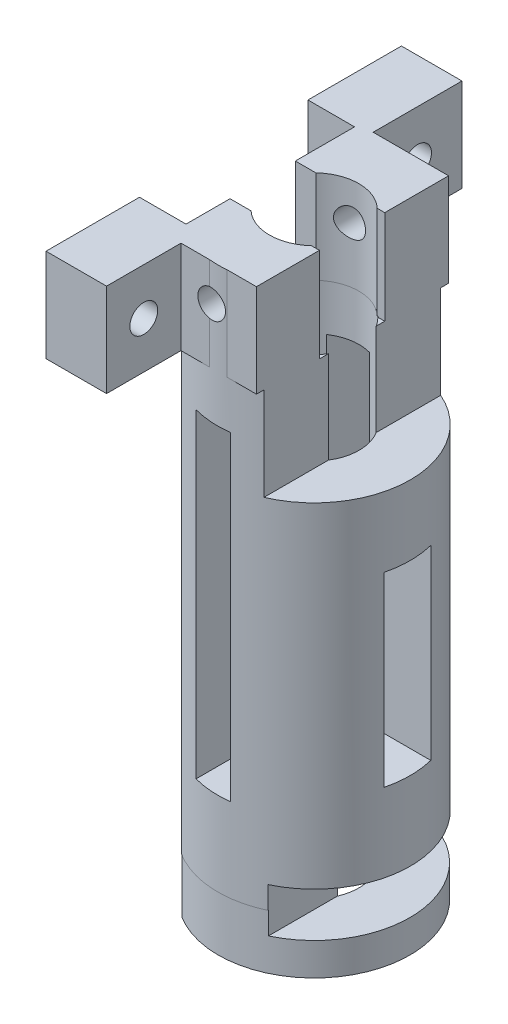
SolidWorks part; units mm, degrees
ref_plane "前基準面" through (0, 0, 0) normal (0, 0, 1) x (1, 0, 0)
ref_plane "上基準面" through (0, 0, 0) normal (0, 1, 0) x (1, 0, 0)
ref_plane "右基準面" through (0, 0, 0) normal (1, 0, 0) x (0, 0, -1)
sketch "草圖1" plane through (0, 0, 0) normal (0, 1, 0) x (1, 0, 0)
  circle A0 centre (0, 0) radius 9.68
  dimension "D1" = 19.36
extrude "伸長-薄件1" add sketch "草圖1" along normal blind 116.68 thin
ref_plane "平面1" through (-21, 0, 0) normal (1, 0, 0) x (0, 0, -1)
sketch "草圖11" plane through (0, 116.68, 0) normal (0, 1, 0) x (1, 0, 0)
  line L0 (-993.1634, -44.2358) -> (49006.8366, -44.2358) construction
  line L2 (35.2085, 30.7642) -> (8.2085, 30.7642)
  line L3 (35.2085, 30.7642) -> (35.2085, -119.2358)
  line L4 (35.2085, -119.2358) -> (8.2085, -119.2358)
  line L5 (8.2085, 30.7642) -> (8.2085, -119.2358)
  line L6 (35.2085, 30.7642) -> (8.2085, -119.2358) construction
  line L7 (35.2085, -119.2358) -> (8.2085, 30.7642) construction
  circle A0 centre (0, 0) radius 20.68 construction
  point P1 (21.7085, -44.2358)
  dimension "D1" = 150
  dimension "D2" = 27
  dimension "D3" = 30.7642
extrude "除料-伸長3" cut sketch "草圖11" against normal blind 40
ref_plane "平面2" through (0, 0, 21) normal (0, 0, 1) x (1, 0, 0)
sketch "草圖13" plane through (0, 0, 21) normal (0, 0, 1) x (1, 0, 0)
  line L0 (-21, -22.649) -> (-21, 22.649) construction
  line L1 (-21, 122.7847) -> (-11, 122.7847)
  line L2 (-21, 122.7847) -> (-21, -5.5603)
  line L3 (-21, -5.5603) -> (-11, -5.5603)
  line L4 (-11, 122.7847) -> (-11, -5.5603)
  dimension "D1" = 10
extrude "除料-伸長7" cut sketch "草圖13" against normal through all
sketch "草圖15" plane through (0, 0, 21) normal (0, 0, 1) x (1, 0, 0)
  line L0 (-1.3957, -883.32) -> (-1.3957, 49116.68) construction
  line L1 (8.2085, 116.68) -> (-11, 116.68) construction
  line L2 (-11, 0) -> (20.68, 0) construction
  line L3 (2.6043, 86.68) -> (-5.3957, 86.68)
  line L4 (2.6043, 86.68) -> (2.6043, 18)
  line L5 (2.6043, 18) -> (-5.3957, 18)
  line L6 (-5.3957, 86.68) -> (-5.3957, 18)
  line L7 (2.6043, 86.68) -> (-5.3957, 18) construction
  line L8 (2.6043, 18) -> (-5.3957, 86.68) construction
  point P1 (-1.3957, 52.34)
  point P5 (-1.3957, 116.68)
  dimension "D1" = 30
  dimension "D2" = 18
  dimension "D3" = 8
extrude "除料-伸長9" cut sketch "草圖15" against normal blind 48
sketch "草圖16" plane through (8.2085, 0, 0) normal (1, 0, 0) x (0, 0, -1)
  line L0 (20.68, 86.68) -> (20.68, 116.68) construction
  line L1 (5.1306, 116.68) -> (20.68, 116.68)
  line L2 (5.1306, 116.68) -> (5.1306, 96.68)
  line L3 (5.1306, 96.68) -> (20.68, 96.68)
  line L4 (20.68, 116.68) -> (20.68, 96.68)
  line L5 (-5.1306, 76.68) -> (-5.1306, 116.68) construction
  line L6 (-5.1306, 96.68) -> (-20.59, 96.68)
  line L7 (-5.1306, 96.68) -> (-5.1306, 116.68)
  line L8 (-5.1306, 116.68) -> (-20.59, 116.68)
  line L9 (-20.59, 96.68) -> (-20.59, 116.68)
  line L10 (-17.5118, 116.68) -> (-20.68, 116.68) construction
  dimension "D1" = 20
extrude "填料-伸長4" add sketch "草圖16" against normal blind 19.2
sketch "草圖17" plane through (0, 116.68, 0) normal (0, 1, 0) x (1, 0, 0)
  line L0 (-1009.59, 0) -> (48990.41, 0) construction
  line L1 (8.2085, 20.68) -> (8.2085, 5.1306) construction
  line L2 (8.2085, 6.97) -> (-11, 6.97)
  line L3 (8.2085, 6.97) -> (8.2085, -7.06)
  line L4 (8.2085, -7.06) -> (-11, -7.06)
  line L5 (-11, 6.97) -> (-11, -7.06)
  line L6 (-11, -17.5118) -> (-11, 17.5118) construction
  line L7 (-10.9915, -20.59) -> (-1.9273, -20.59) construction
  arc A0 (-8.2085, 5.1306) -> (-8.2085, -5.1306) centre (0, 0) ccw construction
  point P6 (-9.68, 0)
  dimension "D1" = 14.03
  dimension "D2" = 13.53
extrude "除料-伸長10" cut sketch "草圖17" against normal blind 20.2
sketch "草圖18" plane through (0, 0, 0) normal (0, -1, 0) x (1, 0, 0)
  circle A0 centre (0, 0) radius 9.59
extrude "除料-伸長11" cut sketch "草圖18" against normal through all
sketch "草圖21" plane through (0, 0, -20.68) normal (0, 0, -1) x (-1, 0, 0)
  line L0 (1.3915, 96.68) -> (1.3915, 105.73) construction
  line L1 (0, 96.68) -> (10.9915, 96.68) construction
  line L2 (1.3915, 105.73) -> (1.3915, 108.73) construction
  circle A0 centre (1.3915, 108.73) radius 2.985
  dimension "D3" = 5.97
  dimension "D1" = 9.05
  dimension "D2" = 3
extrude "除料-伸長12" cut sketch "草圖21" against normal blind 55.2
sketch "草圖23" plane through (0, 0, -20.68) normal (0, 0, -1) x (-1, 0, 0)
  line L0 (1.3915, 105.745) -> (1.3915, -11.785) construction
  circle A0 centre (1.3915, 108.73) radius 2.985 construction
  dimension "D1" = 117.53
sketch "草圖24" plane through (0, 0, 0) normal (0, -1, 0) x (1, 0, 0)
  circle A0 centre (0, 0) radius 9.59
extrude "伸長-薄件2" add sketch "草圖24" along normal blind 55.2 thin
sketch "草圖25" plane through (0, 0, 21) normal (0, 0, 1) x (1, 0, 0)
  line L0 (-1.3915, -11.785) -> (22.6124, -11.785)
  line L1 (22.6124, -11.785) -> (22.6124, -63.8733)
  line L2 (-22.7495, -63.8733) -> (22.6124, -63.8733)
  line L3 (-22.7495, -63.8733) -> (-22.7495, -11.785)
  line L4 (-22.7495, -11.785) -> (-1.3915, -11.785)
extrude "除料-伸長13" cut sketch "草圖25" against normal blind 55.2
sketch "草圖26" plane through (0, 0, 0) normal (0, 1, 0) x (1, 0, 0)
  line L0 (-21, -22.649) -> (-21, 22.649) construction
  line L1 (-10.9915, 20.68) -> (-21, 20.68)
  line L2 (-10.9915, 20.68) -> (-10.9915, -21)
  line L3 (-10.9915, -21) -> (-21, -21)
  line L4 (-21, 20.68) -> (-21, -21)
  line L5 (-17.6, -21) -> (17.6, -21) construction
extrude "除料-伸長15" cut sketch "草圖26" against normal blind 55.2
ref_plane "平面3" through (21, 0, 0) normal (1, 0, 0) x (0, 0, -1)
sketch "草圖27" plane through (21, 0, 0) normal (1, 0, 0) x (0, 0, -1)
  line L0 (0, -923.32) -> (0, 49076.68) construction
  line L1 (5.1306, 76.68) -> (-5.1306, 76.68) construction
  line L2 (18.9811, 76.68) -> (-18.9811, 76.68) construction
  line L3 (-5, 61.68) -> (5, 61.68)
  line L4 (-5, 61.68) -> (-5, 21.68)
  line L5 (-5, 21.68) -> (5, 21.68)
  line L6 (5, 61.68) -> (5, 21.68)
  line L7 (-5, 61.68) -> (5, 21.68) construction
  line L8 (-5, 21.68) -> (5, 61.68) construction
  point P1 (0, 41.68)
  point P5 (0, 76.68)
  dimension "D1" = 15
  dimension "D2" = 40
  dimension "D3" = 10
extrude "除料-伸長16" cut sketch "草圖27" against normal blind 55.2
sketch "草圖28" plane through (21, 0, 0) normal (1, 0, 0) x (0, 0, -1)
  line L1 (-22.4403, 4.804) -> (22.4403, 4.804)
  line L2 (-22.4403, 4.804) -> (-22.4403, -4.804)
  line L3 (-22.4403, -4.804) -> (22.4403, -4.804)
  line L4 (22.4403, 4.804) -> (22.4403, -4.804)
  line L5 (-22.4403, 4.804) -> (22.4403, -4.804) construction
  line L6 (-22.4403, -4.804) -> (22.4403, 4.804) construction
  point P0 (0, 0)
extrude "除料-伸長17" cut sketch "草圖28" against normal blind 12.2
sketch "草圖35" plane through (-10.9915, 0, 0) normal (-1, 0, 0) x (0, 0, 1)
  line L0 (20.59, 116.68) -> (20.59, 96.68)
  line L1 (20.59, 96.68) -> (7.06, 96.68)
  line L2 (7.06, 96.68) -> (7.06, 116.68)
  line L3 (7.06, 116.68) -> (20.59, 116.68)
extrude "填料-伸長10" add sketch "草圖35" along normal blind 15
sketch "草圖36" plane through (-10.9915, 0, 0) normal (-1, 0, 0) x (0, 0, 1)
  line L0 (-20.68, 116.68) -> (-6.97, 116.68)
  line L1 (-6.97, 116.68) -> (-6.97, 96.48)
  line L2 (-6.97, 96.48) -> (-20.68, 96.68)
  line L3 (-20.68, 96.68) -> (-20.68, 116.68)
extrude "填料-伸長11" add sketch "草圖36" along normal blind 15
sketch "草圖37" plane through (0, 0, 20.59) normal (0, 0, 1) x (1, 0, 0)
  line L0 (-25.9915, 96.68) -> (-1.9273, 96.68) construction
  line L1 (-25.9915, 116.68) -> (-16.9915, 116.68)
  line L2 (-25.9915, 116.68) -> (-25.9915, 96.68)
  line L3 (-25.9915, 96.68) -> (-16.9915, 96.68)
  line L4 (-16.9915, 116.68) -> (-16.9915, 96.68)
  dimension "D1" = 9
extrude "填料-伸長12" add sketch "草圖37" along normal blind 20
sketch "草圖38" plane through (0, 0, -20.68) normal (0, 0, -1) x (-1, 0, 0)
  line L0 (25.9915, 116.68) -> (-8.2085, 116.68) construction
  line L1 (25.9915, 96.68) -> (16.9915, 96.68)
  line L2 (25.9915, 96.68) -> (25.9915, 116.68)
  line L3 (25.9915, 116.68) -> (16.9915, 116.68)
  line L4 (16.9915, 96.68) -> (16.9915, 116.68)
  dimension "D1" = 9
extrude "填料-伸長13" add sketch "草圖38" along normal blind 20
sketch "草圖42" plane through (-16.9915, 0, 0) normal (1, 0, 0) x (0, 0, -1)
  line L0 (30.68, -903.32) -> (30.68, 49096.68) construction
  line L1 (40.68, 96.68) -> (20.68, 96.68) construction
  line L2 (-959.32, 106.68) -> (49040.68, 106.68) construction
  line L3 (40.68, 116.68) -> (40.68, 96.68) construction
  line L4 (-30.59, -903.32) -> (-30.59, 49096.68) construction
  line L5 (-40.59, 96.68) -> (-20.59, 96.68) construction
  circle A0 centre (30.68, 106.5544) radius 2.985
  circle A1 centre (-30.3956, 106.68) radius 2.985
  point P5 (30.68, 96.68)
  point P10 (40.68, 106.68)
  point P15 (-30.59, 96.68)
  dimension "D1" = 5.97
  dimension "D2" = 5.97
extrude "除料-伸長21" cut sketch "草圖42" against normal blind 20
sketch "草圖43" plane through (0, 116.68, 0) normal (0, 1, 0) x (1, 0, 0)
  line L0 (-11, 6.97) -> (-10.9915, 20.68)
  line L1 (-10.9915, 20.68) -> (-10.9915, 48.0968)
  line L2 (-10.9915, 48.0968) -> (-28.2748, 48.0968)
  line L3 (-28.2748, 48.0968) -> (-28.2748, -43.2705)
  line L4 (-28.2748, -43.2705) -> (-11, -43.2705)
  line L5 (-11, -43.2705) -> (-11, 6.97)
extrude "除料-伸長23" cut sketch "草圖43" against normal through all
sketch "草圖45" plane through (0, 0, 20.59) normal (0, 0, 1) x (1, 0, 0)
  line L0 (-11, 96.68) -> (-1.9273, 96.68) construction
  line L1 (-11, 116.68) -> (-8, 116.68)
  line L2 (-11, 116.68) -> (-11, 96.68)
  line L3 (-11, 96.68) -> (-8, 96.68)
  line L4 (-8, 116.68) -> (-8, 96.68)
  dimension "D1" = 3
extrude "填料-伸長14" add sketch "草圖45" along normal blind 30
sketch "草圖46" plane through (0, 0, -20.68) normal (0, 0, -1) x (-1, 0, 0)
  line L0 (0, 96.68) -> (10.9915, 96.68) construction
  line L1 (10.9915, 116.68) -> (7.9915, 116.68)
  line L2 (10.9915, 116.68) -> (10.9915, 96.68)
  line L3 (10.9915, 96.68) -> (7.9915, 96.68)
  line L4 (7.9915, 116.68) -> (7.9915, 96.68)
  dimension "D1" = 3
extrude "填料-伸長15" add sketch "草圖46" along normal blind 30
sketch "草圖47" plane through (-11, 0, 0) normal (-1, 0, 0) x (0, 0, 1)
  line L0 (50.59, 116.68) -> (7.06, 116.68) construction
  line L1 (50.59, 96.68) -> (17.5118, 96.68)
  line L2 (50.59, 96.68) -> (50.59, 116.68)
  line L3 (50.59, 116.68) -> (17.5118, 116.68)
  line L4 (17.5118, 96.68) -> (17.5118, 116.68)
extrude "填料-伸長16" add sketch "草圖47" along normal blind 50
sketch "草圖48" plane through (-10.9915, 0, 0) normal (-1, 0, 0) x (0, 0, 1)
  line L1 (-50.68, 116.68) -> (-20.68, 116.68)
  line L2 (-50.68, 116.68) -> (-50.68, 96.68)
  line L3 (-50.68, 96.68) -> (-20.68, 96.68)
  line L4 (-20.68, 116.68) -> (-20.68, 96.68)
extrude "填料-伸長17" add sketch "草圖48" along normal blind 50
sketch "草圖50" plane through (0, 0, 17.5118) normal (0, 0, -1) x (-1, 0, 0)
  line L0 (11, 96.68) -> (11, 116.68)
  line L1 (11, 116.68) -> (61, 116.68)
  line L2 (61, 116.68) -> (61, 96.68)
  line L3 (61, 96.68) -> (11, 96.68)
extrude "填料-伸長18" add sketch "草圖50" along normal blind 1
sketch "草圖51" plane through (0, 0, -20.68) normal (0, 0, 1) x (1, 0, 0)
  line L0 (-10.9915, 116.68) -> (-10.9915, 96.68)
  line L1 (-10.9915, 96.68) -> (-60.9915, 96.68)
  line L2 (-60.9915, 96.68) -> (-60.9915, 116.68)
  line L3 (-60.9915, 116.68) -> (-10.9915, 116.68)
extrude "填料-伸長19" add sketch "草圖51" along normal blind 1
sketch "草圖52" plane through (0, 116.68, 0) normal (0, 1, 0) x (1, 0, 0)
  line L0 (-34.4915, -949.32) -> (-34.4915, 49050.68) construction
  line L1 (-60.9915, 50.68) -> (-7.9915, 50.68) construction
  line L2 (-1007.9915, 35.68) -> (48992.0085, 35.68) construction
  line L3 (-7.9915, 50.68) -> (-7.9915, 20.68) construction
  line L4 (-60.9915, 19.68) -> (-60.9915, 50.68) construction
  line L5 (-7.9915, 50.68) -> (-60.9915, 50.68)
  line L6 (-7.9915, 50.68) -> (-7.9915, 36.68)
  line L7 (-7.9915, 36.68) -> (-60.9915, 36.68)
  line L8 (-60.9915, 50.68) -> (-60.9915, 36.68)
  point P5 (-34.4915, 50.68)
  point P10 (-7.9915, 35.68)
  dimension "D1" = 14
extrude "除料-伸長24" cut sketch "草圖52" against normal through all
sketch "草圖53" plane through (0, 116.68, 0) normal (0, 1, 0) x (1, 0, 0)
  line L0 (-61, -50.59) -> (-61, -16.5118) construction
  line L1 (-8, -50.59) -> (-61, -50.59)
  line L2 (-8, -50.59) -> (-8, -36.59)
  line L3 (-8, -36.59) -> (-61, -36.59)
  line L4 (-61, -50.59) -> (-61, -36.59)
  dimension "D1" = 14
extrude "除料-伸長25" cut sketch "草圖53" against normal through all
sketch "草圖54" plane through (0, 116.68, 0) normal (0, 1, 0) x (1, 0, 0)
  line L0 (-60.9915, 36.68) -> (-7.9915, 36.68) construction
  line L1 (-61, -36.59) -> (-21, -36.59)
  line L2 (-61, -36.59) -> (-61, 36.68)
  line L3 (-61, 36.68) -> (-21, 36.68)
  line L4 (-21, -36.59) -> (-21, 36.68)
  dimension "D1" = 40
extrude "除料-伸長26" cut sketch "草圖54" against normal through all
sketch "草圖55" plane through (0, 116.68, 0) normal (0, 1, 0) x (1, 0, 0)
  line L0 (-15.0276, -36.59) -> (-15.0276, -16.5118) construction
  line L1 (-8, -36.59) -> (-21, -36.59) construction
  line L2 (-21, -16.5118) -> (-11, -16.5118) construction
  line L3 (-13.4574, 19.68) -> (-13.4574, 39.76) construction
  line L4 (-10.9921, 19.68) -> (-21, 19.68) construction
  dimension "D1" = 20.08
sketch "草圖56" plane through (0, 0, -36.68) normal (0, 0, -1) x (-1, 0, 0)
  line L1 (7.9915, 96.68) -> (21, 96.68)
  line L2 (7.9915, 96.68) -> (7.9915, 116.68)
  line L3 (7.9915, 116.68) -> (21, 116.68)
  line L4 (21, 96.68) -> (21, 116.68)
extrude "填料-伸長21" add sketch "草圖56" along normal blind 3.08
sketch "草圖57" plane through (-7.9915, 0, 0) normal (1, 0, 0) x (0, 0, -1)
  line L0 (30.22, -903.32) -> (30.22, 49096.68) construction
  line L1 (39.76, 96.68) -> (20.68, 96.68) construction
  line L2 (-960.24, 106.68) -> (49039.76, 106.68) construction
  line L3 (39.76, 116.68) -> (39.76, 96.68) construction
  line L4 (-28.59, -903.32) -> (-28.59, 49096.68) construction
  line L5 (-36.59, 96.68) -> (-20.59, 96.68) construction
  circle A0 centre (30.22, 106.6344) radius 2.985
  circle A1 centre (-28.59, 106.68) radius 2.985
  point P5 (30.22, 96.68)
  point P10 (39.76, 106.68)
  point P15 (-28.59, 96.68)
  dimension "D1" = 5.97
  dimension "D2" = 5.97
extrude "除料-伸長27" cut sketch "草圖57" against normal through all
